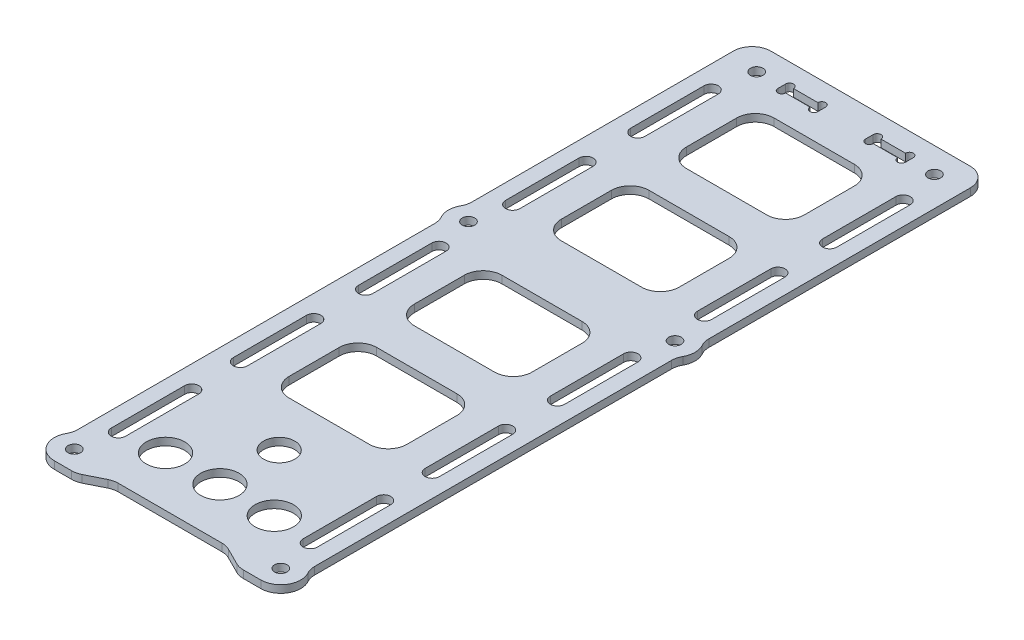
SolidWorks part; units mm, degrees
material "Thornel Mat VMA"
ref_plane "Front Plane" through (0, 0, 0) normal (0, 0, 1) x (1, 0, 0)
ref_plane "Top Plane" through (0, 0, 0) normal (0, 1, 0) x (1, 0, 0)
ref_plane "Right Plane" through (0, 0, 0) normal (1, 0, 0) x (0, 0, -1)
sketch "Sketch1" plane through (0, 0, 0) normal (0, 1, 0) x (1, 0, 0)
  line L0 (-16.51, -144.7038) -> (-11.43, -142.1638)
  line L1 (-20.2311, 0) -> (20.2311, 0)
  line L2 (-24.0411, -3.81) -> (-24.0411, -144.7038)
  line L3 (-24.0411, -144.7038) -> (24.0411, -144.7038)
  line L4 (24.0411, -3.81) -> (24.0411, -144.7038)
  line L5 (-11.43, -142.1638) -> (11.43, -142.1638)
  line L6 (11.43, -142.1638) -> (16.51, -144.7038)
  line L7 (0, -144.7038) -> (0, 0) construction
  line L8 (-20.955, -60.6425) -> (20.955, -60.6425) construction
  line L9 (-18.034, -5.08) -> (18.034, -5.08) construction
  line L10 (-20.955, -140.6398) -> (20.955, -140.6398) construction
  circle A0 centre (20.955, -60.6425) radius 4.064
  circle A1 centre (-20.955, -60.6425) radius 4.064
  circle A2 centre (-20.955, -60.6425) radius 1.27
  circle A3 centre (20.955, -60.6425) radius 1.27
  circle A4 centre (-18.034, -5.08) radius 1.27
  circle A5 centre (18.034, -5.08) radius 1.27
  circle A6 centre (-20.955, -140.6398) radius 4.064
  circle A7 centre (20.955, -140.6398) radius 4.064
  circle A8 centre (-20.955, -140.6398) radius 1.27
  circle A9 centre (20.955, -140.6398) radius 1.27
  arc A10 (24.0411, -3.81) -> (20.2311, 0) centre (20.2311, -3.81) ccw
  arc A11 (-20.2311, 0) -> (-24.0411, -3.81) centre (-20.2311, -3.81) ccw
  point P4 (0, 0)
  point P15 (0, -60.6425)
  point P23 (0, -5.08)
  point P28 (0, -140.6398)
  point P35 (-24.0411, 0)
  dimension "D6" = 50.038
  dimension "D7" = 41.91
  dimension "D10" = 2.54
  dimension "D12" = 3.81
  dimension "D13" = 8.128
  dimension "D1" = 144.7038
  dimension "D2" = 48.0822
  dimension "D3" = 2.54
  dimension "D4" = 22.86
  dimension "D5" = 33.02
  dimension "D8" = 36.068
  dimension "D9" = 5.08
  dimension "D11" = 60.6425
extrude "MAIN BODY" add sketch "Sketch1" along normal blind 1.524
sketch "Sketch2" plane through (0, 1.524, 0) normal (0, 1, 0) x (1, 0, 0)
  line L0 (8.89, -5.08) -> (8.89, -8.9269) construction
  line L6 (-18.034, -5.08) -> (18.034, -5.08) construction
  line L8 (4.826, -4.2863) -> (12.954, -4.2863)
  line L9 (4.826, -4.2863) -> (4.826, -5.8738)
  line L10 (4.826, -5.8738) -> (12.954, -5.8738)
  line L11 (12.954, -4.2863) -> (12.954, -5.8738)
  line L12 (4.826, -4.2863) -> (12.954, -5.8738) construction
  line L13 (4.826, -5.8738) -> (12.954, -4.2863) construction
  line L14 (0, -144.7038) -> (0, 0) construction
  line L15 (0, -144.7038) -> (0, 0) construction
  circle A0 centre (5.6197, -5.8738) radius 0.7937
  circle A1 centre (5.6197, -4.2863) radius 0.7937
  circle A2 centre (12.1602, -4.2863) radius 0.7937
  circle A3 centre (12.1602, -5.8738) radius 0.7937
  point P3 (8.89, -5.08)
  dimension "D6" = 1.5875
  dimension "D1" = 8.128
  dimension "D2" = 1.5875
  dimension "D3" = 8.89
extrude "CAMERA PLATE SLOTS" cut sketch "Sketch2" against normal through all contours A3 | A2 | L8 L11 L10 L9 | A1 | A0
mirror "Mirror2" about plane through (0, 0, 0) normal (1, 0, 0) of "CAMERA PLATE SLOTS"
sketch "Sketch4" plane through (0, 1.524, 0) normal (0, 1, 0) x (1, 0, 0)
  line L0 (19.4691, -12.8778) -> (19.4691, -27.7622) construction
  line L1 (20.9169, -12.8778) -> (20.9169, -27.7622)
  line L2 (18.0213, -12.8778) -> (18.0213, -27.7622)
  line L3 (24.0411, -3.81) -> (24.0411, -144.7038) construction
  line L4 (-20.2311, 0) -> (20.2311, 0) construction
  arc A0 (20.9169, -12.8778) -> (18.0213, -12.8778) centre (19.4691, -12.8778) ccw
  arc A1 (18.0213, -27.7622) -> (20.9169, -27.7622) centre (19.4691, -27.7622) ccw
  point P2 (19.4691, -20.32)
  dimension "D2" = 17.78
  dimension "D1" = 2.8956
  dimension "D3" = 3.1242
  dimension "D4" = 11.43
extrude "LONG SLOT CUTOUT" cut sketch "Sketch4" against normal through all contours L2 A1 L1 A0
mirror "Mirror1" about plane through (0, 0, 0) normal (1, 0, 0) of "LONG SLOT CUTOUT"
sketch "Sketch3" plane through (0, 1.524, 0) normal (0, 1, 0) x (1, 0, 0)
  line L0 (0, -144.7038) -> (0, 0) construction
  line L1 (-8.1407, -29.21) -> (8.1407, -29.21)
  line L2 (-11.9507, -25.4) -> (-11.9507, -15.24)
  line L3 (-8.1407, -11.43) -> (8.1407, -11.43)
  line L4 (11.9507, -25.4) -> (11.9507, -15.24)
  line L5 (-11.9507, -29.21) -> (11.9507, -11.43) construction
  line L6 (-11.9507, -11.43) -> (11.9507, -29.21) construction
  line L7 (-20.2311, 0) -> (20.2311, 0) construction
  arc A0 (-11.9507, -25.4) -> (-8.1407, -29.21) centre (-8.1407, -25.4) ccw
  arc A1 (8.1407, -29.21) -> (11.9507, -25.4) centre (8.1407, -25.4) ccw
  arc A2 (11.9507, -15.24) -> (8.1407, -11.43) centre (8.1407, -15.24) ccw
  arc A3 (-8.1407, -11.43) -> (-11.9507, -15.24) centre (-8.1407, -15.24) ccw
  point P0 (0, -20.32)
  dimension "D4" = 3.81
  dimension "D1" = 17.78
  dimension "D2" = 23.9014
  dimension "D3" = 11.43
extrude "RECTANGLE CUTOUT" cut sketch "Sketch3" against normal through all
pattern_linear "LPattern1" count 2 spacing 25.4 along (0, 0, 1) of "LONG SLOT CUTOUT", "Mirror1", "RECTANGLE CUTOUT"
pattern_linear "LPattern2" count 2 spacing 55.245 along (0, 0, 1) of "LPattern1", "LONG SLOT CUTOUT", "Mirror1", "RECTANGLE CUTOUT"
pattern_linear "LPattern3" count 2 spacing 105.41 along (0, 0, 1) of "LONG SLOT CUTOUT", "Mirror1"
sketch "Sketch5" plane through (0, 1.524, 0) normal (0, 1, 0) x (1, 0, 0)
  line L0 (0, -144.7038) -> (0, 0) construction
  line L1 (-11.0363, -132.0419) -> (0, -132.0419) construction
  line L2 (0, -132.0419) -> (11.0363, -132.0419) construction
  line L3 (-11.43, -142.1638) -> (11.43, -142.1638) construction
  circle A0 centre (0, -132.0419) radius 3.8989
  circle A1 centre (11.0363, -132.0419) radius 3.8989
  circle A2 centre (-11.0363, -132.0419) radius 3.8989
  circle A3 centre (0, -120.015) radius 3.175
  dimension "D2" = 7.7978
  dimension "D3" = 29.8704
  dimension "D4" = 6.35
  dimension "D5" = 4.953
  dimension "D1" = 6.223
extrude "ROUND CUTOUTS" cut sketch "Sketch5" against normal through all
fillet "Fillet1" radius 3.81 10 edges at (24.0411, 0.762, 57.9982) (24.0411, 0.762, 63.2868) (24.0411, 0.762, 137.9955) (16.51, 0.762, 144.7038) (11.43, 0.762, 142.1638) (-11.43, 0.762, 142.1638) (-16.51, 0.762, 144.7038) (-24.0411, 0.762, 137.9955) (-24.0411, 0.762, 63.2868) (-24.0411, 0.762, 57.9982)
